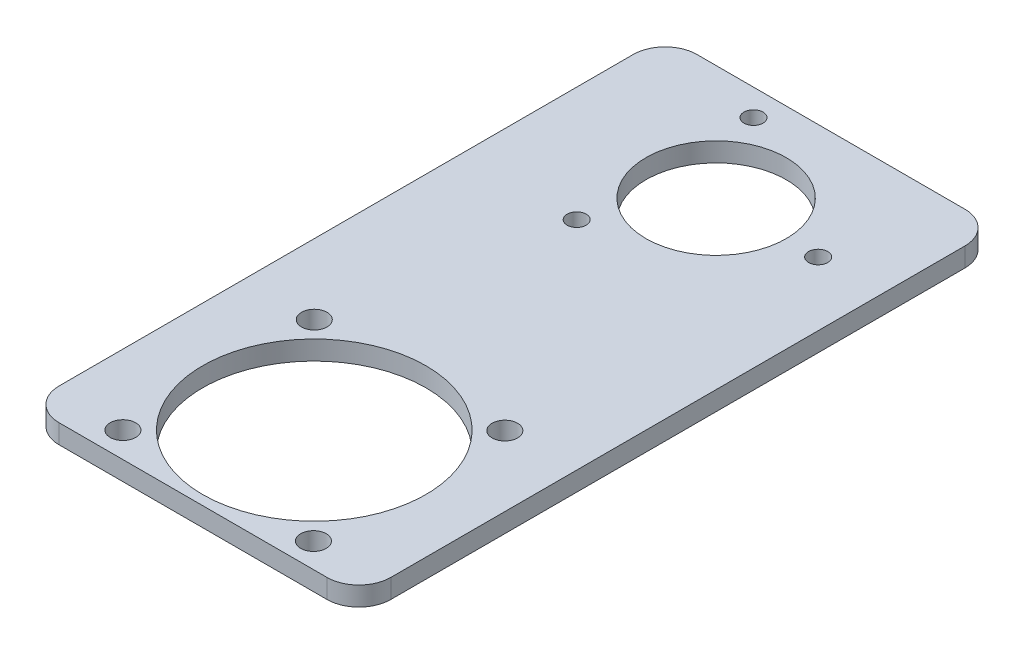
SolidWorks part; units mm, degrees
ref_plane "Front Plane" through (0, 0, 0) normal (0, 0, 1) x (1, 0, 0)
ref_plane "Top Plane" through (0, 0, 0) normal (0, 1, 0) x (1, 0, 0)
ref_plane "Right Plane" through (0, 0, 0) normal (1, 0, 0) x (0, 0, -1)
sketch "Sketch1" plane through (0, 0, 0) normal (0, 1, 0) x (1, 0, 0)
  line L0 (-8, 45.8564) -> (0, 32)
  line L1 (-21, -50) -> (21, -50)
  line L2 (-26, -45) -> (-26, 45)
  line L3 (-21, 50) -> (21, 50)
  line L4 (26, -45) -> (26, 45)
  line L5 (-26, -50) -> (26, 50) construction
  line L6 (-26, 50) -> (26, -50) construction
  line L7 (0, 32) -> (-8, 18.1436)
  line L8 (0, 32) -> (16, 32)
  circle A0 centre (0, -31) radius 17.5
  circle A1 centre (-15, -16) radius 2
  circle A2 centre (14.9997, -16.1252) radius 2
  circle A3 centre (14.9997, -46.1252) radius 2
  circle A4 centre (-15, -46) radius 2
  arc A5 (21, -50) -> (26, -45) centre (21, -45) ccw
  arc A6 (-21, -50) -> (-26, -45) centre (-21, -45) cw
  arc A7 (26, 45) -> (21, 50) centre (21, 45) ccw
  arc A8 (-21, 50) -> (-26, 45) centre (-21, 45) ccw
  circle A9 centre (0, 32) radius 11
  circle A10 centre (16, 32) radius 1.5
  circle A11 centre (-8, 45.8564) radius 1.5
  circle A12 centre (-8, 18.1436) radius 1.5
  point P0 (0, 0)
  point P38 (0, 32)
  point P43 (0, -50)
  dimension "D3" = 35
  dimension "D4" = 4
  dimension "D10" = 5
  dimension "D14" = 22
  dimension "D15" = 16
  dimension "D16" = 16
  dimension "D21" = 3
  dimension "D22" = 3
  dimension "D23" = 3
  dimension "D1" = 100
  dimension "D2" = 52
  dimension "D5" = 30
  dimension "D6" = 30
  dimension "D7" = 30
  dimension "D8" = 11
  dimension "D9" = 11
  dimension "D11" = 30
  dimension "D12" = 15
  dimension "D13" = 19
  dimension "D17" = 16
  dimension "D18" = 120
  dimension "D19" = 63
  dimension "D20" = 120
extrude "Boss-Extrude1" add sketch "Sketch1" along normal blind 3
